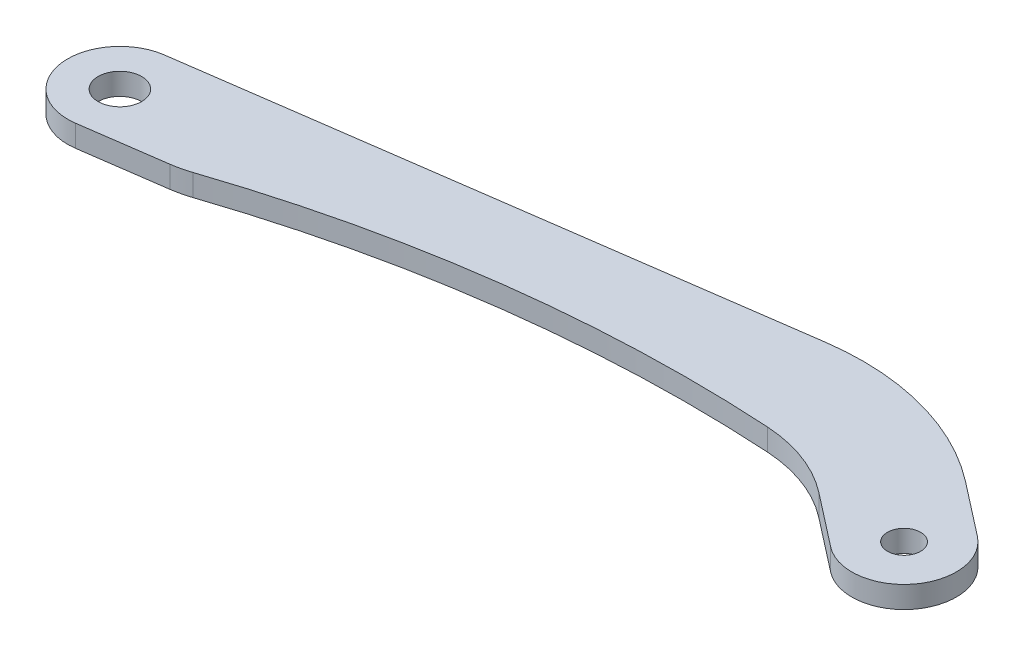
SolidWorks part; units mm, degrees
ref_plane "Front Plane" through (0, 0, 0) normal (0, 0, 1) x (1, 0, 0)
ref_plane "Top Plane" through (0, 0, 0) normal (0, 1, 0) x (1, 0, 0)
ref_plane "Right Plane" through (0, 0, 0) normal (1, 0, 0) x (0, 0, -1)
sketch "Sketch1" plane through (0, 0, 0) normal (0, 1, 0) x (1, 0, 0)
  line L0 (0, 0) -> (114.3, 0) construction
  line L1 (57.15, 698.5) -> (57.15, -698.5) construction
  circle A0 centre (0, 0) radius 2.54
  circle A1 centre (114.3, 0) radius 3.175
  arc A2 (0, -7.62) -> (0, 7.62) centre (0, 0) cw
  arc A3 (114.3, -7.62) -> (114.3, 7.62) centre (114.3, 0) ccw
  arc A4 (0, 7.62) -> (114.3, 7.62) centre (57.15, 698.5) ccw
  arc A5 (0, -7.62) -> (114.3, -7.62) centre (57.15, -698.5) cw
  point P12 (57.15, 0)
  dimension "D2" = 6.35
  dimension "D3" = 5.08
  dimension "D5" = 7.62
  dimension "D1" = 114.3
  dimension "D4" = 1397
extrude "Boss-Extrude1" [suppressed] add sketch "Sketch1" along normal blind 3.175
sketch "Sketch2" plane through (0, 0, 0) normal (0, 1, 0) x (1, 0, 0)
  line L0 (-57.15, 0) -> (57.15, 0) construction
  line L1 (-56.0852, -7.5452) -> (28.3331, 4.3685)
  line L2 (-58.2148, 7.5452) -> (26.2034, 19.4589)
  line L3 (52.4732, -6.016) -> (44.7346, 0)
  line L4 (54.0882, 12.0319) -> (61.8268, 6.016)
  circle A0 centre (-57.15, 0) radius 3.175
  circle A1 centre (57.15, 0) radius 2.413
  arc A2 (-57.15, -7.62) -> (-57.15, 7.62) centre (-57.15, 0) cw
  arc A3 (57.15, -7.62) -> (57.15, 7.62) centre (57.15, 0) ccw
  arc A5 (-57.15, -7.62) -> (57.15, -7.62) centre (0, -813.9212) cw construction
  arc A6 (-57.15, -7.62) -> (-56.0852, -7.5452) centre (-57.15, 0) ccw
  arc A8 (57.15, -7.62) -> (52.4732, -6.016) centre (57.15, 0) cw
  arc A15 (44.7346, 0) -> (28.3331, 4.3685) centre (31.3749, -17.1851) ccw
  arc A16 (26.2034, 19.4589) -> (54.0882, 12.0319) centre (31.3749, -17.1851) cw
  arc A17 (32.6964, 4.5419) -> (-41.2617, -5.1944) centre (20.8078, -190.9164) ccw
  arc A18 (-41.2617, -5.1944) -> (-44.002, -5.84) centre (-46.1626, 9.47) cw
  point P10 (0, 0)
  dimension "D2" = 4.826
  dimension "D3" = 6.35
  dimension "D4" = 7.62
  dimension "D1" = 114.3
extrude "Boss-Extrude2" add sketch "Sketch2" along normal blind 3.175
